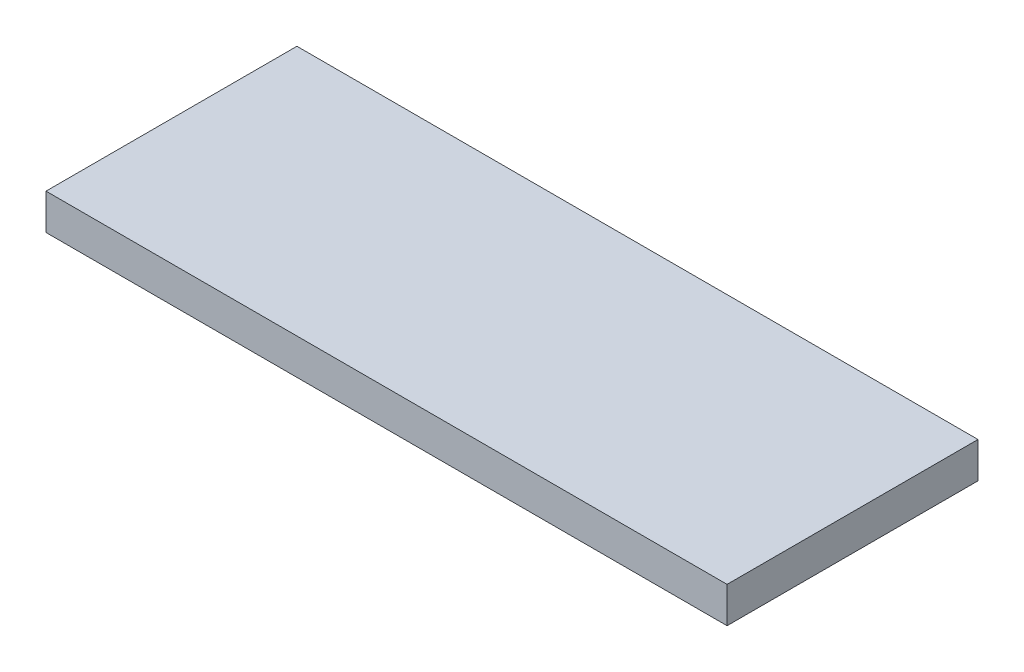
SolidWorks part; units mm, degrees
ref_plane "Ebene vorne" through (0, 0, 0) normal (0, 0, 1) x (1, 0, 0)
ref_plane "Ebene oben" through (0, 0, 0) normal (0, 1, 0) x (1, 0, 0)
ref_plane "Ebene rechts" through (0, 0, 0) normal (1, 0, 0) x (0, 0, -1)
sketch "Skizze1" plane through (0, 0, 0) normal (1, 0, 0) x (0, 0, -1)
  line L1 (0, 0) -> (350, 0)
  line L2 (0, 0) -> (0, 50)
  line L3 (0, 50) -> (350, 50)
  line L4 (350, 0) -> (350, 50)
  dimension "D1" = 50
  dimension "D2" = 350
extrude "Aufsatz-Linear austragen1" add sketch "Skizze1" along normal blind 950
